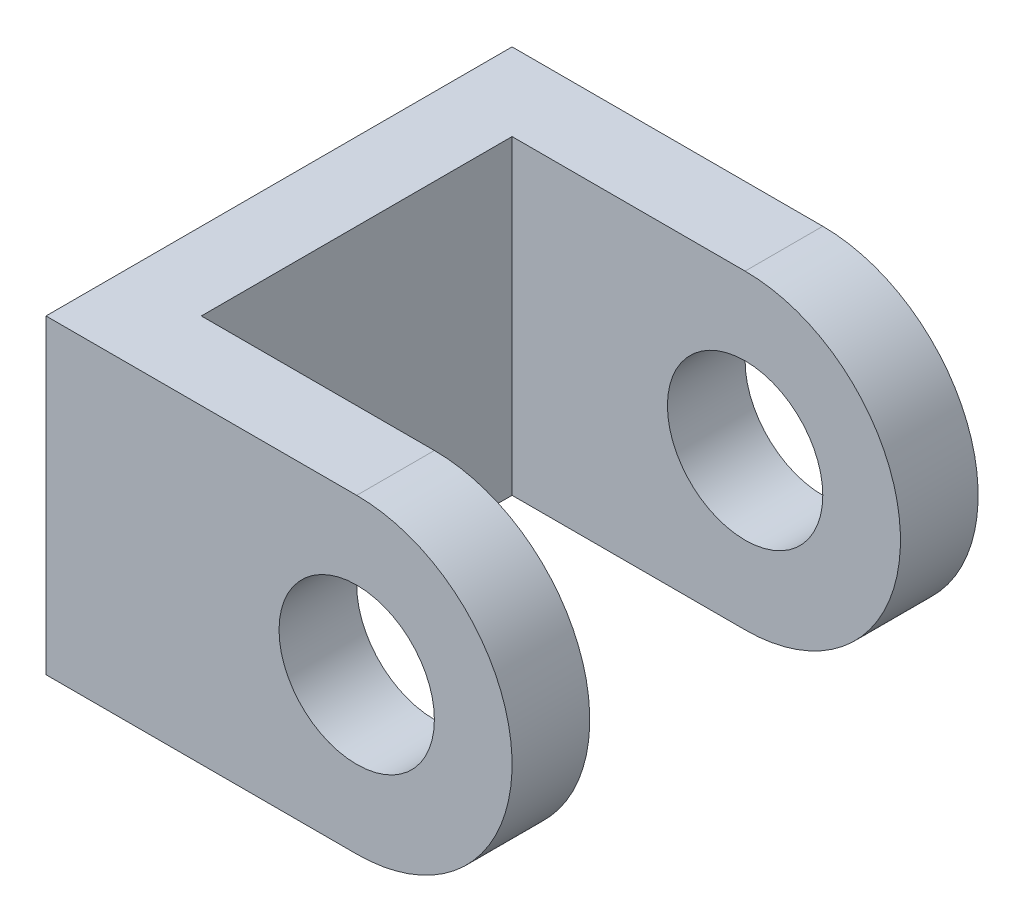
SolidWorks part; units mm, degrees
ref_plane "Front Plane" through (0, 0, 0) normal (0, 0, 1) x (1, 0, 0)
ref_plane "Top Plane" through (0, 0, 0) normal (0, 1, 0) x (1, 0, 0)
ref_plane "Right Plane" through (0, 0, 0) normal (1, 0, 0) x (0, 0, -1)
sketch "Sketch1" plane through (0, 0, 0) normal (0, 0, 1) x (1, 0, 0)
  line L1 (-10, 10) -> (10, 10)
  line L2 (-10, 10) -> (-10, -10)
  line L3 (-10, -10) -> (10, -10)
  line L5 (-10, 10) -> (10, -10) construction
  line L6 (-10, -10) -> (10, 10) construction
  arc A0 (10, 10) -> (10, -10) centre (10, 0) cw
  circle A1 centre (10, 0) radius 5
  point P0 (0, 0)
  dimension "D2" = 10
  dimension "D1" = 20
extrude "Boss-Extrude1" add sketch "Sketch1" against normal blind 30
ref_plane "Plane1" through (20, 0, 0) normal (1, 0, 0) x (0, 0, -1)
sketch "Sketch2" plane through (20, 0, 0) normal (1, 0, 0) x (0, 0, -1)
  line L0 (30, 10) -> (0, 10) construction
  line L1 (25, 10) -> (5, 10)
  line L2 (25, 10) -> (25, -10)
  line L3 (25, -10) -> (5, -10)
  line L4 (5, 10) -> (5, -10)
  line L5 (30, -10) -> (0, -10) construction
  line L6 (0, 10) -> (0, -10) construction
  line L7 (30, -10) -> (30, 10) construction
  dimension "D1" = 5
  dimension "D2" = 5
extrude "Cut-Extrude1" cut sketch "Sketch2" against normal blind 25
